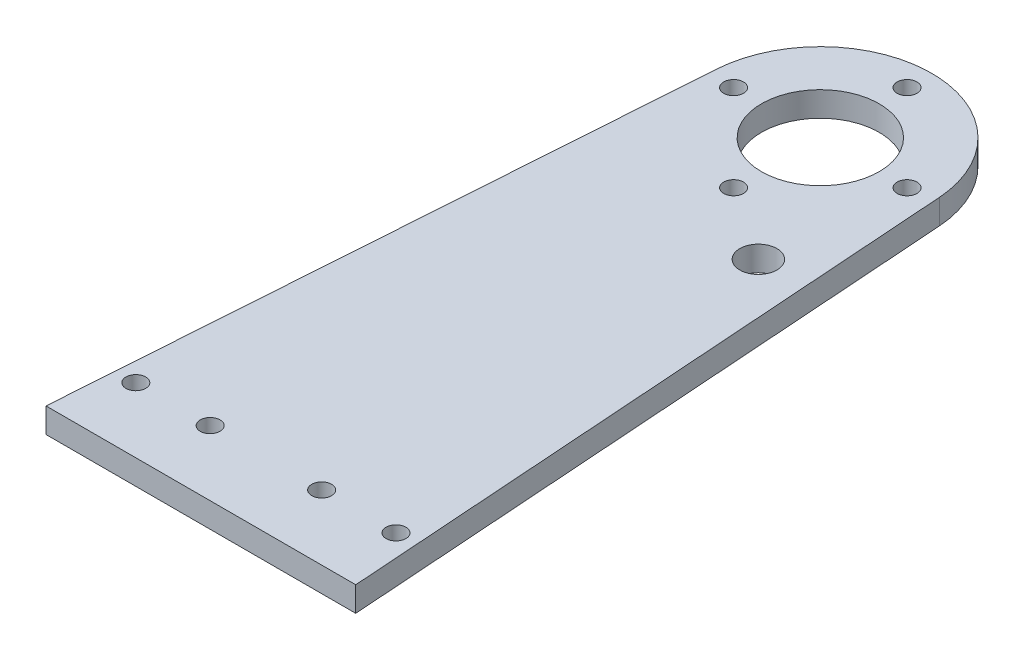
SolidWorks part; units mm, degrees
ref_plane "前视基准面" through (0, 0, 0) normal (0, 0, 1) x (1, 0, 0)
ref_plane "上视基准面" through (0, 0, 0) normal (0, 1, 0) x (1, 0, 0)
ref_plane "右视基准面" through (0, 0, 0) normal (1, 0, 0) x (0, 0, -1)
sketch "草图1" plane through (0, 0, 0) normal (0, 1, 0) x (1, 0, 0)
  line L0 (-25, -100) -> (25, -100)
  line L1 (-17.9566, 1.2492) -> (-25, -100)
  line L2 (17.9566, 1.2492) -> (25, -100)
  circle A0 centre (0, 0) radius 9.5
  circle A1 centre (-14, 0) radius 1.6
  circle A2 centre (0, -14) radius 1.6
  circle A3 centre (14, 0) radius 1.6
  circle A4 centre (0, 14) radius 1.6
  circle A5 centre (9, -89.5) radius 1.6
  circle A6 centre (21, -89.5) radius 1.6
  circle A7 centre (-21, -89.5) radius 1.6
  circle A8 centre (-9, -89.5) radius 1.6
  arc A9 (17.9566, 1.2492) -> (-17.9566, 1.2492) centre (0, 0) ccw
  circle A10 centre (12, -22) radius 3
  dimension "D1" = 19
extrude "凸台-拉伸1" add sketch "草图1" along normal blind 4
